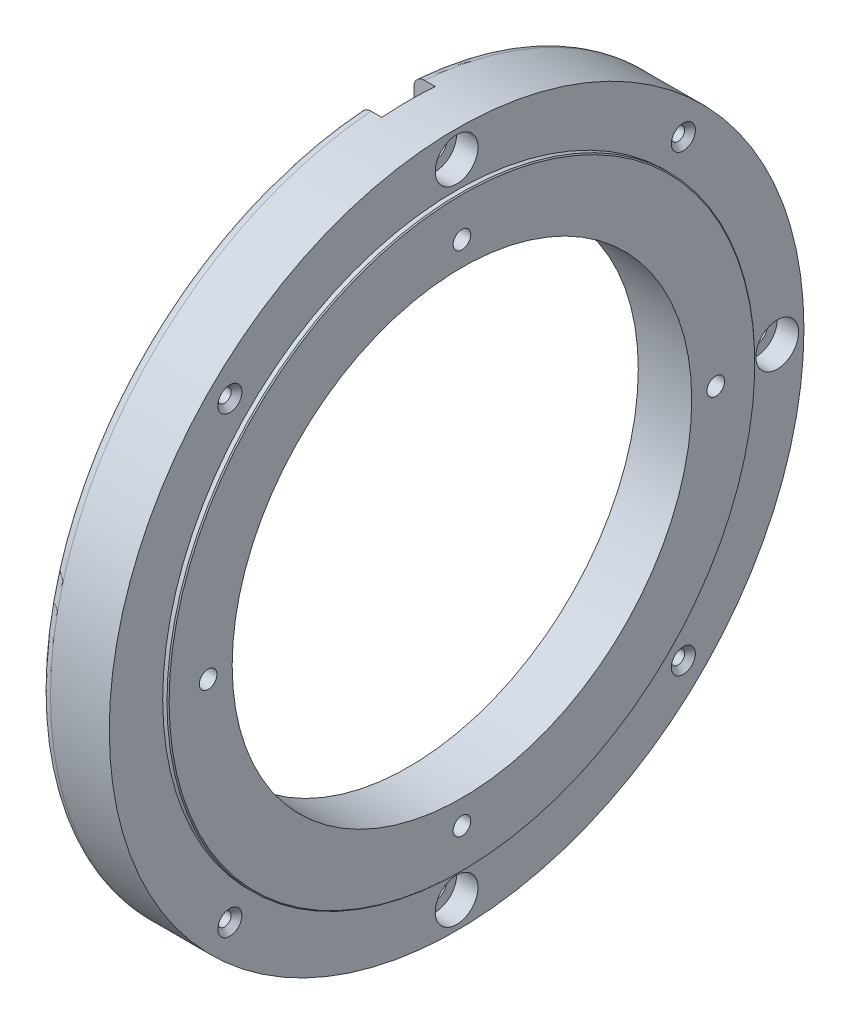
SolidWorks part; units mm, degrees
material "Alliage 6061"
ref_plane "Face" through (0, 0, 0) normal (0, 0, 1) x (1, 0, 0)
ref_plane "Dessus" through (0, 0, 0) normal (0, 1, 0) x (1, 0, 0)
ref_plane "Droite" through (0, 0, 0) normal (1, 0, 0) x (0, 0, -1)
sketch "Esquisse1" plane through (0, 0, 0) normal (0, 0, 1) x (1, 0, 0)
  line L0 (0, 0) -> (54.7909, 0) construction
  line L1 (0, 55) -> (0, 65)
  line L2 (0, 65) -> (13, 65)
  line L3 (13, 65) -> (13, 55)
  line L4 (13, 55) -> (14, 55)
  line L5 (0, 55) -> (4, 55)
  line L6 (4, 55) -> (4, 43)
  line L7 (4, 43) -> (14, 43)
  line L8 (14, 55) -> (14, 43)
  dimension "D1" = 86
  dimension "D2" = 110
  dimension "D3" = 4
  dimension "D4" = 130
  dimension "D5" = 13
  dimension "D6" = 110
  dimension "D7" = 1
revolve "Révolution1" add sketch "Esquisse1" angle 360 about L0
fillet "Congé1" radius 2 1 edges at (0, 0, 65)
chamfer "Chanfrein1" distance 0.5 angle 45 1 edges at (0, 0, 55)
sketch "Esquisse5" plane through (0, 0, 0) normal (-1, 0, 0) x (0, 0, 1)
  line L0 (-5, 80) -> (-5, 5)
  line L1 (5, 5) -> (5, -5)
  line L2 (5, 80) -> (5, 5)
  line L4 (-5, 80) -> (5, 80)
  line L5 (-5, -80) -> (5, -80)
  line L6 (-80, 5) -> (-5, 5)
  line L7 (-80, -5) -> (-5, -5)
  line L9 (-80, 5) -> (-80, -5)
  line L11 (5, -5) -> (5, -80)
  line L12 (-5, -5) -> (-5, -80)
  dimension "D1" = 5
  dimension "D2" = 5
  dimension "D3" = 5
  dimension "D4" = 5
extrude "Enlèv. mat.-Extru.1" cut sketch "Esquisse5" against normal blind 4
sketch "Esquisse6" plane through (14, 0, 0) normal (1, 0, 0) x (0, 0, -1)
  line L0 (0, 60) -> (0, -60) construction
  line L1 (-60, 0) -> (60, 0) construction
  line L2 (-42.4264, -42.4264) -> (0, 0) construction
  line L3 (0, 0) -> (42.4264, 42.4264) construction
  line L4 (-42.4264, 42.4264) -> (0, 0) construction
  line L5 (0, 0) -> (42.4264, -42.4264) construction
  circle A0 centre (0, 0) radius 60 construction
  circle A1 centre (0, 0) radius 47.5 construction
  dimension "D1" = 120
  dimension "D2" = 95
  dimension "D3" = 45
  dimension "D4" = 45
hole_wizard "Trou taraudé M41" positions "Esquisse8" profile "Esquisse7" tap size "M4" standard "Iso" end condition through all
sketch "Esquisse8" plane through (14, 0, 0) normal (1, 0, 0) x (0, 0, -1)
  line L0 (0, 60) -> (0, -60) construction
  line L1 (-60, 0) -> (60, 0) construction
  circle A0 centre (0, 0) radius 47.5 construction
  point P0 (0, 47.5)
  point P6 (47.5, 0)
  point P10 (0, -47.5)
  point P12 (-47.5, 0)
cosmetic thread "Filetage de perçage1" parameters "D2"=4
cosmetic thread "Filetage de perçage2" parameters "D2"=4
cosmetic thread "Filetage de perçage3" parameters "D2"=4
cosmetic thread "Filetage de perçage4" parameters "D2"=4
sketch "Esquisse7" plane through (14, 47.5, 0) normal (0, 1, 0) x (0, 0, -1)
  line L0 (0, 0) -> (0, 14)
  line L1 (0, 14) -> (1.65, 14)
  line L2 (1.65, 14) -> (1.65, 0)
  line L5 (1.65, 0) -> (0, 0)
  line L11 (0, -6.35) -> (0, 107.95) construction
  dimension "Diamètre du trou pour taraudage jusqu'au prochain" = 3.3
  dimension "Profondeur du trou pour taraudage jusqu'au prochain" = 14
hole_wizard "Chambrage pour vis à tête hexagonale M41" positions "Esquisse10" profile "Esquisse9" counterbore size "M4" standard "Iso" end condition through all
sketch "Esquisse10" plane through (14, 0, 0) normal (1, 0, 0) x (0, 0, -1)
  point P0 (0, 60)
  point P3 (60, 0)
  point P6 (0, -60)
sketch "Esquisse9" plane through (14, 60, 0) normal (0, 1, 0) x (0, 0, -1)
  line L0 (0, 0) -> (0, 14)
  line L1 (0, 14) -> (2.15, 14)
  line L3 (2.15, 14) -> (2.15, 5)
  line L4 (2.15, 5) -> (4, 5)
  line L5 (4, 5) -> (4, 0)
  line L7 (4, 0) -> (0, 0)
  line L11 (0, -6.35) -> (0, 107.95) construction
  dimension "Diamètre du perçage jusqu'au prochain" = 4.3
  dimension "Profondeur du perçage jusqu'au prochain" = 14
  dimension "Diamètre du chambrage" = 8
  dimension "Profondeur du chambrage" = 5
chamfer "Chanfrein2" distance 0.2 angle 45 1 edges at (14, 0, 55)
hole_wizard "Trou taraudé M31" positions "Esquisse14" profile "Esquisse13" tap size "M3" standard "Iso" end condition up to next
sketch "Esquisse14" plane through (13, 0, 0) normal (1, 0, 0) x (0, 0, -1)
  point P0 (42.4264, 42.4264)
  point P3 (42.4264, -42.4264)
  point P6 (-42.4264, -42.4264)
  point P9 (-42.4264, 42.4264)
cosmetic thread "Filetage de perçage9" parameters "D2"=3
cosmetic thread "Filetage de perçage10" parameters "D2"=3
cosmetic thread "Filetage de perçage11" parameters "D2"=3
cosmetic thread "Filetage de perçage12" parameters "D2"=3
sketch "Esquisse13" plane through (13, 42.4264, -42.4264) normal (0, 1, 0) x (0, 0, -1)
  line L0 (0, 0) -> (0, 13)
  line L1 (0, 13) -> (1.25, 13)
  line L2 (1.25, 13) -> (1.25, 1)
  line L3 (1.25, 1) -> (2.25, 0)
  line L5 (2.25, 0) -> (0, 0)
  line L6 (-1.25, 1) -> (-2.25, 0) construction
  line L11 (0, -6.35) -> (0, 107.95) construction
  dimension "Diamètre du trou pour taraudage jusqu'au prochain" = 2.5
  dimension "Profondeur du trou pour taraudage jusqu'au prochain" = 13
  dimension "Diamètre du fraisage entrant" = 4.5
  dimension "Angle du fraisage entrant" = 90
